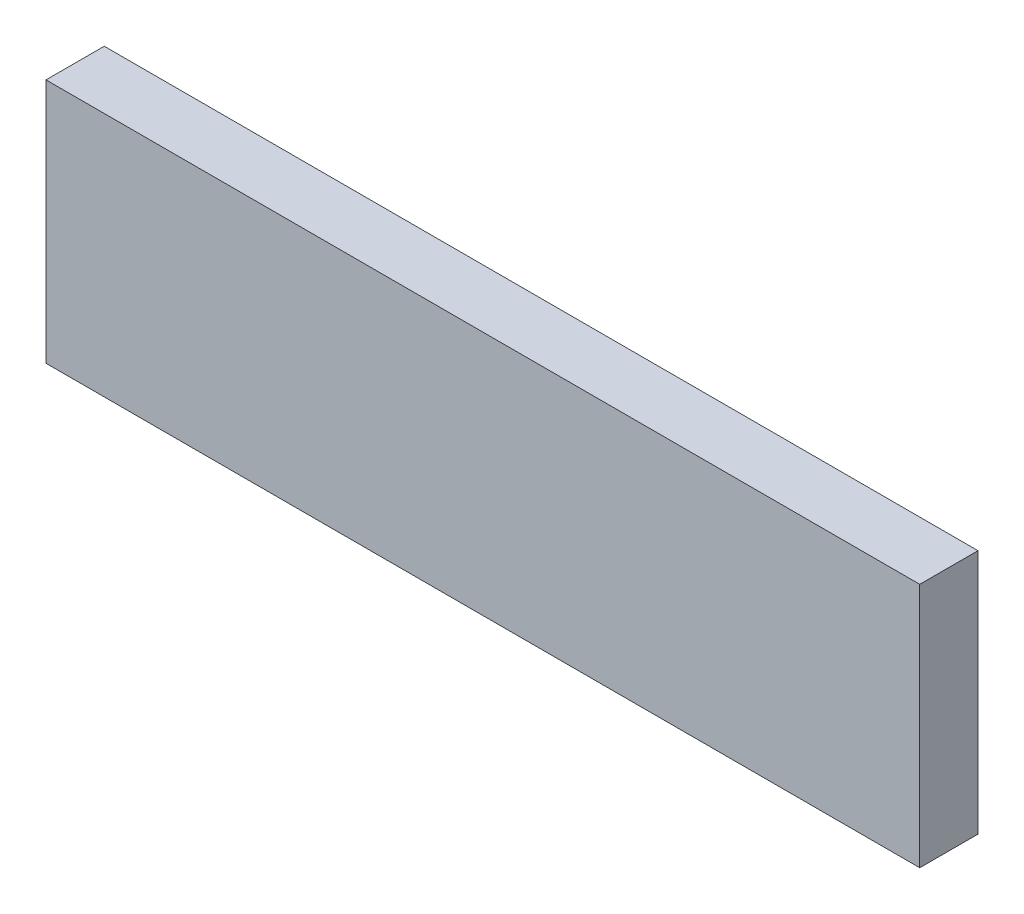
SolidWorks part; units mm, degrees
ref_plane "前视基准面" through (0, 0, 0) normal (0, 0, 1) x (1, 0, 0)
ref_plane "上视基准面" through (0, 0, 0) normal (0, 1, 0) x (1, 0, 0)
ref_plane "右视基准面" through (0, 0, 0) normal (1, 0, 0) x (0, 0, -1)
sketch "草图1" plane through (0, 0, 0) normal (0, 0, 1) x (1, 0, 0)
  line L1 (0, 0) -> (105, 0)
  line L2 (0, 0) -> (0, -29.5)
  line L3 (0, -29.5) -> (105, -29.5)
  line L4 (105, 0) -> (105, -29.5)
  dimension "D1" = 29.5
  dimension "D2" = 105
extrude "凸台-拉伸1" add sketch "草图1" along normal blind 7
